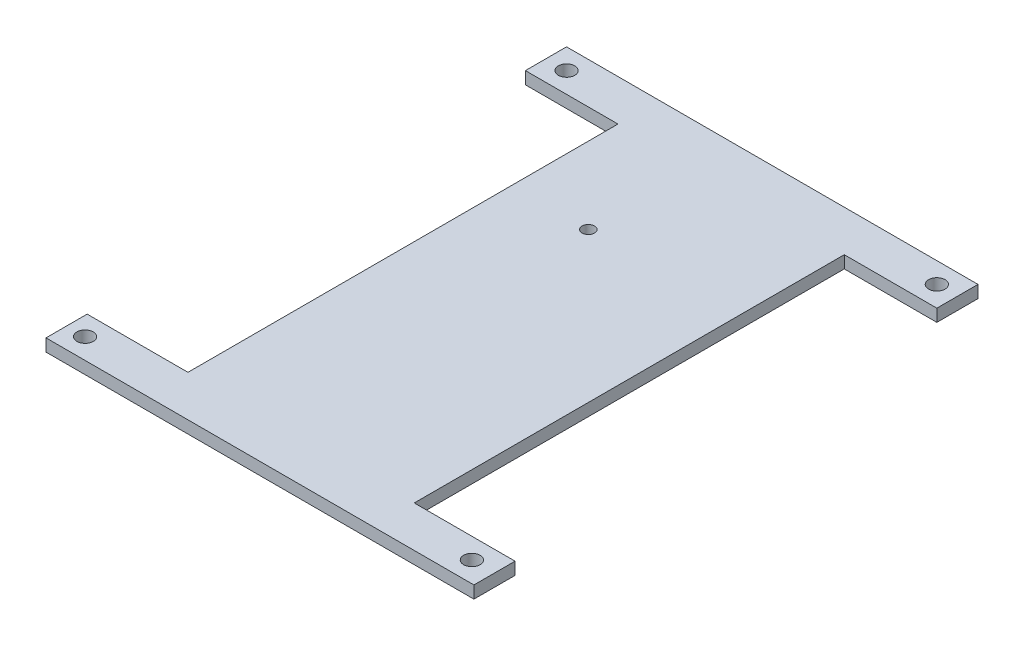
SolidWorks part; units mm, degrees
ref_plane "Alzado" through (0, 0, 0) normal (0, 0, 1) x (1, 0, 0)
ref_plane "Planta" through (0, 0, 0) normal (0, 1, 0) x (1, 0, 0)
ref_plane "Vista lateral" through (0, 0, 0) normal (1, 0, 0) x (0, 0, -1)
sketch "Croquis1" plane through (0, 0, 0) normal (0, 1, 0) x (1, 0, 0)
  circle A0 centre (0, 0) radius 75
  dimension "D1" = 150
extrude "Saliente-Extruir1" add sketch "Croquis1" along normal blind 3
sketch "Croquis3" plane through (0, 3, 0) normal (0, 1, 0) x (1, 0, 0)
  line L0 (0, 0) -> (0, 75) construction
  circle A0 centre (0, 0) radius 75 construction
sketch "Croquis5" plane through (0, 3, 0) normal (0, 1, 0) x (1, 0, 0)
  line L0 (0, 75) -> (0, 55) construction
  line L1 (0, 0) -> (0, 75) construction
  line L2 (-75, 0) -> (-27.5, 0) construction
  line L3 (0, 55) -> (-53, 55)
  line L4 (0, 55) -> (0, 77)
  line L5 (0, 77) -> (-53, 77)
  line L6 (-53, 55) -> (-53, 77)
  line L7 (0, 55) -> (53, 55)
  line L8 (0, 55) -> (0, 77)
  line L9 (0, 77) -> (53, 77)
  line L10 (53, 55) -> (53, 77)
  line L11 (75, 0) -> (27.5, 0) construction
  line L13 (-27.5, 0) -> (-77.5, 0)
  line L14 (-27.5, 0) -> (-27.5, -70)
  line L15 (-27.5, -70) -> (-77.5, -70)
  line L16 (-77.5, 0) -> (-77.5, -70)
  line L17 (-27.5, 0) -> (-77.5, 0)
  line L18 (-27.5, 0) -> (-27.5, 55)
  line L19 (-27.5, 55) -> (-77.5, 55)
  line L20 (-77.5, 0) -> (-77.5, 55)
  line L21 (75, 0) -> (27.5, 0)
  line L22 (75, 0) -> (75, 55)
  line L23 (75, 55) -> (27.5, 55)
  line L24 (27.5, 0) -> (27.5, 55)
  line L25 (27.5, 0) -> (75, 0)
  line L26 (27.5, 0) -> (27.5, -70)
  line L27 (27.5, -70) -> (75, -70)
  line L28 (75, 0) -> (75, -70)
  line L29 (-27.5, -78) -> (27.5, -78)
  line L30 (-27.5, -78) -> (-27.5, -49.51)
  line L31 (-27.5, -49.51) -> (27.5, -49.51)
  line L32 (27.5, -78) -> (27.5, -49.51)
  circle A0 centre (0, 0) radius 75 construction
  dimension "D1" = 20
  dimension "D2" = 53
  dimension "D3" = 22
  dimension "D4" = 53
  dimension "D5" = 47.5
  dimension "D6" = 47.5
  dimension "D7" = 55
  dimension "D8" = 50
  dimension "D9" = 70
  dimension "D10" = 70
  dimension "D11" = 8
  dimension "D12" = 28.49
  dimension "D13" = 90
  dimension "D14" = 55
extrude "Cortar-Extruir10" cut sketch "Croquis5" against normal through all
sketch "Croquis10" plane through (0, 3, 0) normal (0, 1, 0) x (1, 0, 0)
  line L1 (-50, 55) -> (50, 55)
  line L2 (-50, 55) -> (-50, 65)
  line L3 (-50, 65) -> (50, 65)
  line L4 (50, 55) -> (50, 65)
  line L7 (-27.5, -49.51) -> (-27.5, 55) construction
  line L9 (27.5, 55) -> (-27.5, 55) construction
  circle A0 centre (-45, 60) radius 2
  circle A1 centre (45, 60) radius 2
  dimension "D3" = 4
  dimension "D4" = 5
  dimension "D5" = 5
  dimension "D6" = 4
  dimension "D7" = 5
  dimension "D8" = 5
  dimension "D1" = 100
  dimension "D2" = 10
  dimension "D9" = 22.5
extrude "Saliente-Extruir2" add sketch "Croquis10" against normal blind 3
sketch "Croquis12" plane through (0, 3, 0) normal (0, 1, 0) x (1, 0, 0)
  line L1 (-52, -59.51) -> (52, -59.51)
  line L2 (-52, -59.51) -> (-52, -49.51)
  line L3 (-52, -49.51) -> (52, -49.51)
  line L4 (52, -59.51) -> (52, -49.51)
  line L5 (-27.5, -49.51) -> (27.5, -49.51) construction
  circle A0 centre (-47.5, -54.51) radius 2
  circle A1 centre (46.5, -54.51) radius 2
  dimension "D5" = 4
  dimension "D6" = 4.5
  dimension "D7" = 5
  dimension "D8" = 4
  dimension "D9" = 5
  dimension "D10" = 5.5
  dimension "D1" = 104
  dimension "D2" = 24.5
  dimension "D3" = 10
  dimension "D4" = 10
extrude "Saliente-Extruir3" add sketch "Croquis12" against normal blind 3
sketch "Croquis13" plane through (0, 3, 0) normal (0, 1, 0) x (1, 0, 0)
  line L0 (-27.5, 55) -> (-8.9, 55) construction
  line L1 (-8.9, 65) -> (-8.9, 29.2) construction
  line L2 (50, 65) -> (-50, 65) construction
  circle A0 centre (-8.9, 29.2) radius 1.5
  dimension "D3" = 3
  dimension "D1" = 18.6
  dimension "D2" = 35.8
extrude "Cortar-Extruir11" cut sketch "Croquis13" against normal through all
